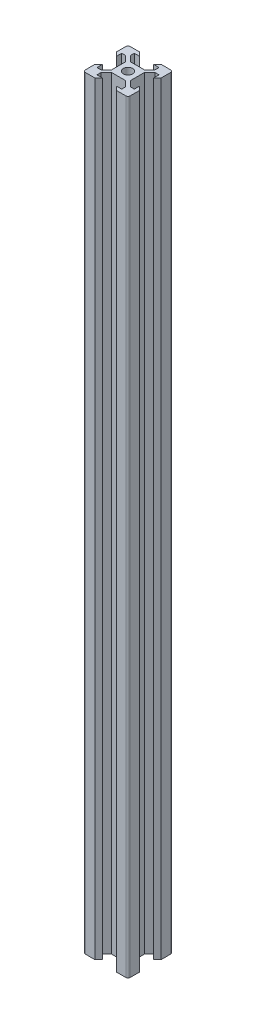
SolidWorks part; units mm, degrees
material "1060 Alloy"
ref_plane "Front Plane" through (0, 0, 0) normal (0, 0, 1) x (1, 0, 0)
ref_plane "Top Plane" through (0, 0, 0) normal (0, 1, 0) x (1, 0, 0)
ref_plane "Right Plane" through (0, 0, 0) normal (1, 0, 0) x (0, 0, -1)
ref_plane "End Plane" through (0, 340, 0) normal (0, 1, 0) x (1, 0, 0)
sketch "MasterLayoutSketch" plane through (0, 0, 0) normal (0, 1, 0) x (1, 0, 0)
  line L0 (-8.325, 3.1) -> (-8.325, 5.5)
  line L1 (-10, -10) -> (10, -10) construction
  line L2 (-10, -10) -> (-10, 10) construction
  line L3 (-10, 10) -> (10, 10) construction
  line L4 (10, -10) -> (10, 10) construction
  line L5 (-10, -10) -> (10, 10) construction
  line L6 (-10, 10) -> (10, -10) construction
  line L7 (-4.775, 10) -> (-3.1, 8.325)
  line L10 (-8.325, 5.5) -> (-6.5607, 5.5)
  line L11 (-10, 4.775) -> (-8.325, 3.1)
  line L12 (-5.5, 8.325) -> (-5.5, 6.5607)
  line L13 (-3.1, 8.325) -> (-5.5, 8.325)
  line L14 (-10, 10) -> (-10, 4.775)
  line L19 (3.1, 8.325) -> (5.5, 8.325)
  line L20 (10, 4.775) -> (8.325, 3.1)
  line L21 (-10, 10) -> (-4.775, 10)
  line L22 (-6.5607, 5.5) -> (-4.1607, 3.1)
  line L23 (-5.5, 6.5607) -> (-3.1, 4.1607)
  line L24 (5.5, 8.325) -> (5.5, 6.5607)
  line L25 (4.775, 10) -> (3.1, 8.325)
  line L26 (8.325, 5.5) -> (6.5607, 5.5)
  line L27 (8.325, 3.1) -> (8.325, 5.5)
  line L28 (10, 10) -> (4.775, 10)
  line L29 (10, 10) -> (10, 4.775)
  line L30 (5.5, 6.5607) -> (3.1, 4.1607)
  line L31 (6.5607, 5.5) -> (4.1607, 3.1)
  line L32 (8.325, -3.1) -> (8.325, -5.5)
  line L33 (4.775, -10) -> (3.1, -8.325)
  line L34 (8.325, -5.5) -> (6.5607, -5.5)
  line L35 (10, -4.775) -> (8.325, -3.1)
  line L36 (5.5, -8.325) -> (5.5, -6.5607)
  line L37 (3.1, -8.325) -> (5.5, -8.325)
  line L38 (10, -10) -> (10, -4.775)
  line L39 (10, -10) -> (4.775, -10)
  line L40 (6.5607, -5.5) -> (4.1607, -3.1)
  line L41 (5.5, -6.5607) -> (3.1, -4.1607)
  line L42 (-3.1, -8.325) -> (-5.5, -8.325)
  line L43 (-10, -4.775) -> (-8.325, -3.1)
  line L44 (-5.5, -8.325) -> (-5.5, -6.5607)
  line L45 (-4.775, -10) -> (-3.1, -8.325)
  line L46 (-8.325, -5.5) -> (-6.5607, -5.5)
  line L47 (-8.325, -3.1) -> (-8.325, -5.5)
  line L48 (-10, -10) -> (-4.775, -10)
  line L49 (-10, -10) -> (-10, -4.775)
  line L50 (-5.5, -6.5607) -> (-3.1, -4.1607)
  line L51 (-6.5607, -5.5) -> (-4.1607, -3.1)
  line L52 (-4.1607, 3.1) -> (-4.1607, -3.1)
  line L53 (-3.1, -4.1607) -> (3.1, -4.1607)
  line L54 (4.1607, -3.1) -> (4.1607, 3.1)
  line L55 (-3.1, 4.1607) -> (3.1, 4.1607)
  circle A0 centre (0, 0) radius 2.1
  point P0 (0, 0)
  point P9 (0, 0)
  dimension "D6" = 4.2
  dimension "D1" = 20
  dimension "D2" = 4
  dimension "D3" = 11
  dimension "D4" = 9.55
  dimension "D5" = 6.2
  dimension "D7" = 1.5
extrude "Main Extrusion" add sketch "MasterLayoutSketch" along normal up to surface (340 mm away) up to plane "End Plane"
fillet "Edge Fillets" radius 1 4 edges at (10, 170, -10) (10, 170, 10) (-10, 170, 10) (-10, 170, -10)
